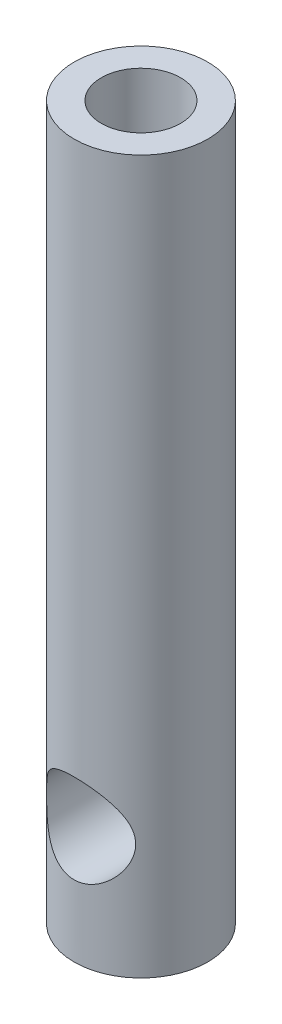
SolidWorks part; units mm, degrees
ref_plane "Front Plane" through (0, 0, 0) normal (0, 0, 1) x (1, 0, 0)
ref_plane "Top Plane" through (0, 0, 0) normal (0, 1, 0) x (1, 0, 0)
ref_plane "Right Plane" through (0, 0, 0) normal (1, 0, 0) x (0, 0, -1)
sketch "Sketch1" plane through (0, 0, 0) normal (0, 1, 0) x (1, 0, 0)
  circle A0 centre (0, 0) radius 1.905
  dimension "D1" = 3.81
extrude "Boss-Extrude1" add sketch "Sketch1" against normal blind 20.32
hole_wizard "#4-40 Tapped Hole1" positions "Sketch3" profile "Sketch2" tap size "#4-40" standard "ANSI Inch"
sketch "Sketch3" plane through (0, 0, 0) normal (0, 1, 0) x (1, 0, 0)
  point P0 (0, 0)
sketch "Sketch2" plane through (0, 0, 0) normal (1, 0, 0) x (0, 0, 1)
  line L0 (0, 0) -> (0, 8.2992)
  line L1 (0, 8.2992) -> (1.1303, 7.62)
  line L2 (1.1303, 7.62) -> (1.1303, 0)
  line L5 (1.1303, 0) -> (0, 0)
  line L10 (0, 8.2992) -> (-1.1303, 7.62) construction
  line L11 (0, -6.35) -> (0, 107.95) construction
  dimension "Tap Drill Dia." = 2.2606
  dimension "Tap Drill Depth" = 7.62
  dimension "Drill Angle" = 118
cosmetic thread "Hole Thread1" parameters "D1"=5.588, "D2"=2.8448
sketch "Sketch4" plane through (0, 0, 0) normal (0, 0, 1) x (1, 0, 0)
  line L0 (0, 0) -> (0, -3.3855) construction
  circle A0 centre (0, -17.018) radius 1.27
  dimension "D1" = 2.54
  dimension "D2" = 17.018
extrude "Cut-Extrude1" cut sketch "Sketch4" against normal through all and the other way through all
